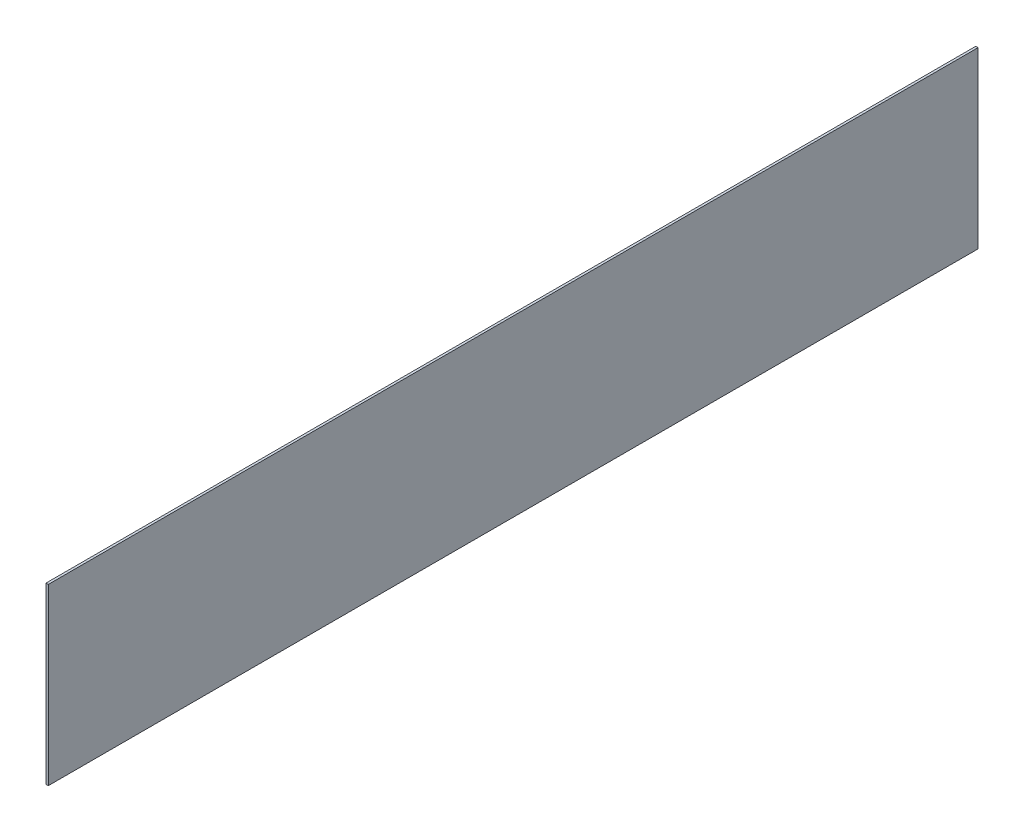
SolidWorks part; units mm, degrees
material "Acrylic (Medium-high impact)"
ref_plane "Front Plane" through (0, 0, 0) normal (0, 0, 1) x (1, 0, 0)
ref_plane "Top Plane" through (0, 0, 0) normal (0, 1, 0) x (1, 0, 0)
ref_plane "Right Plane" through (0, 0, 0) normal (1, 0, 0) x (0, 0, -1)
sketch "Sketch1" plane through (0, 0, 0) normal (0, 0, 1) x (1, 0, 0)
  line L1 (-38.3333, 292.5) -> (-28.3333, 292.5)
  line L2 (-38.3333, 292.5) -> (-38.3333, -457.5)
  line L3 (-38.3333, -457.5) -> (-28.3333, -457.5)
  line L4 (-28.3333, 292.5) -> (-28.3333, -457.5)
  dimension "D1" = 750
  dimension "D2" = 10
extrude "Boss-Extrude1" add sketch "Sketch1" along normal blind 4000
